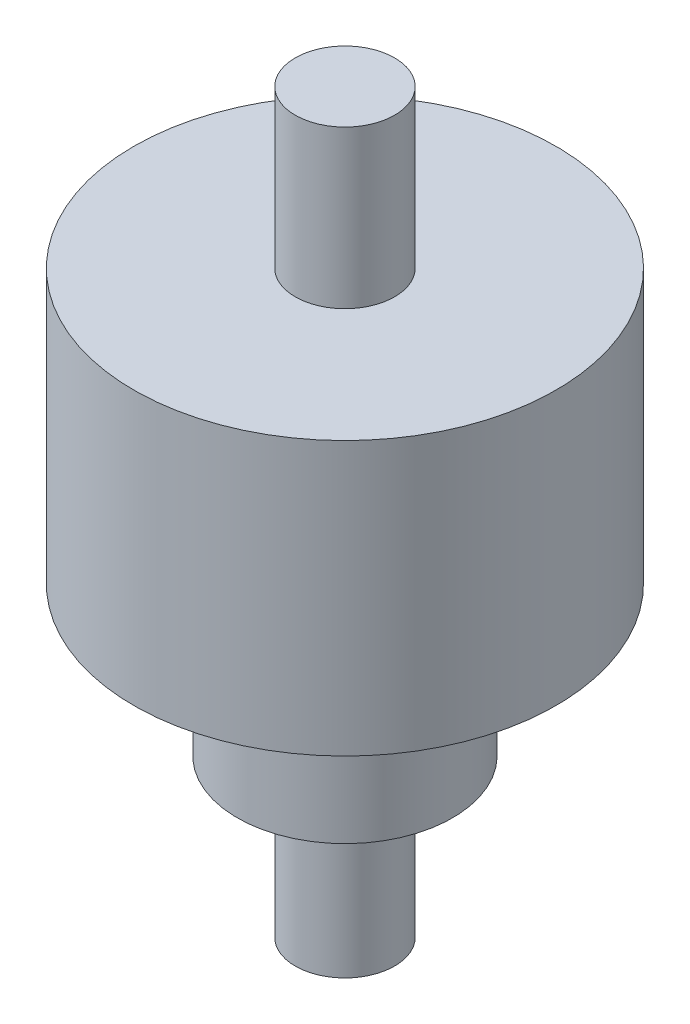
SolidWorks part; units mm, degrees
ref_plane "Front Plane" through (0, 0, 0) normal (0, 0, 1) x (1, 0, 0)
ref_plane "Top Plane" through (0, 0, 0) normal (0, 1, 0) x (1, 0, 0)
ref_plane "Right Plane" through (0, 0, 0) normal (1, 0, 0) x (0, 0, -1)
sketch "Sketch1" plane through (0, 0, 0) normal (0, 0, 1) x (1, 0, 0)
  line L0 (0, 0) -> (0, 86460.5299) construction
  line L1 (25.5, 0) -> (25.5, 33)
  line L2 (25.5, 0) -> (13, 0)
  line L3 (13, 0) -> (13, -18)
  line L4 (13, -18) -> (6, -18)
  line L5 (6, -18) -> (6, -37)
  line L6 (6, -37) -> (0, -37)
  line L7 (25.5, 33) -> (6, 33)
  line L8 (6, 33) -> (6, 52)
  line L9 (6, 52) -> (0, 52)
  line L10 (25.5, -1) -> (0, -1) construction
  line L11 (25.5, 16) -> (0, 16) construction
  line L12 (12.75, -1) -> (12.75, 16) construction
  line L13 (12.75, 16) -> (12.75, 33) construction
  line L14 (0, 52) -> (0, -37)
  point P5 (9.5, -18)
  dimension "D1" = 51
  dimension "D2" = 26
  dimension "D3" = 12
  dimension "D4" = 19
  dimension "D5" = 70
  dimension "D6" = 17
  dimension "D7" = 16
revolve "Revolve1" add sketch "Sketch1" angle 360 about L14
